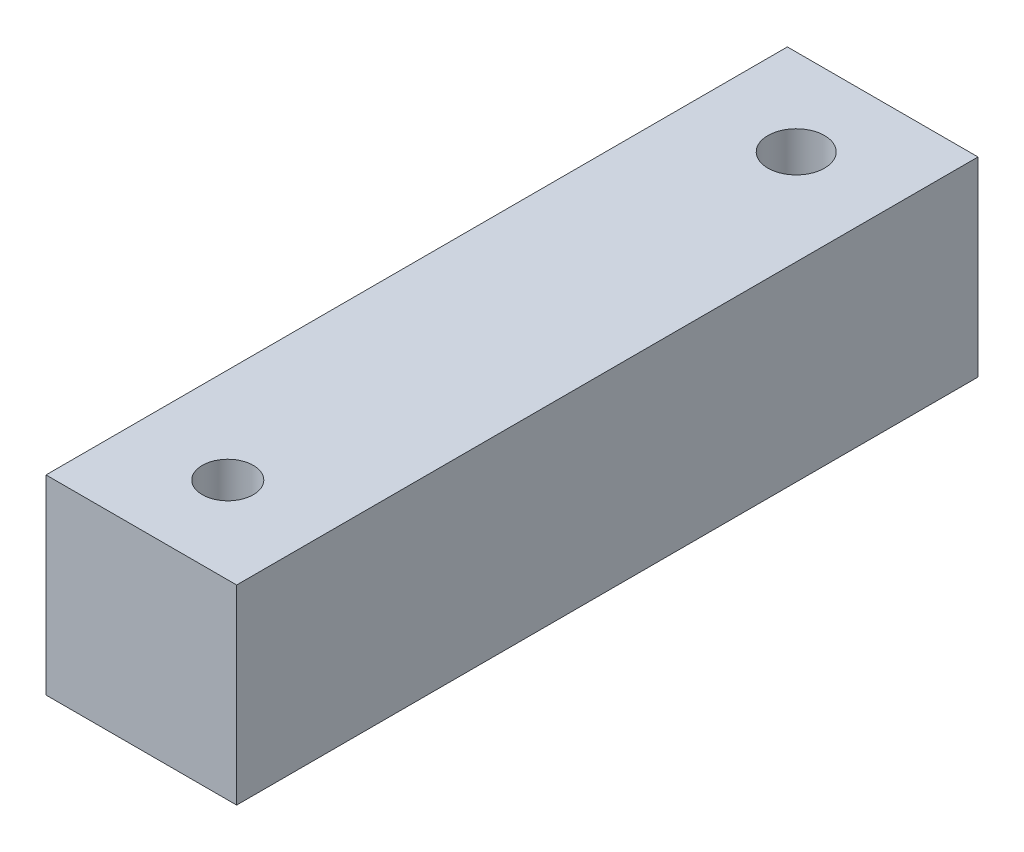
SolidWorks part; units mm, degrees
ref_plane "Plan de face" through (0, 0, 0) normal (0, 0, 1) x (1, 0, 0)
ref_plane "Plan de dessus" through (0, 0, 0) normal (0, 1, 0) x (1, 0, 0)
ref_plane "Plan de droite" through (0, 0, 0) normal (1, 0, 0) x (0, 0, -1)
sketch "Esquisse1" plane through (0, 0, 0) normal (0, 0, 1) x (1, 0, 0)
  line L1 (0, 18) -> (18, 18)
  line L2 (0, 18) -> (0, 0)
  line L3 (0, 0) -> (18, 0)
  line L4 (18, 18) -> (18, 0)
  dimension "D1" = 18
extrude "Boss.-Extru.1" add sketch "Esquisse1" along normal blind 70
sketch "Esquisse4" plane through (0, 18, 0) normal (0, 1, 0) x (1, 0, 0)
  line L0 (18, -70) -> (0, -70) construction
  line L1 (9, -61.836) -> (9, -70) construction
  line L2 (9, -8.164) -> (9, 0) construction
  line L3 (18, 0) -> (0, 0) construction
  circle A0 centre (9, -61.836) radius 2.4071
  circle A1 centre (9, -8.164) radius 2.6729
extrude "Enlèv. mat.-Extru.1" cut sketch "Esquisse4" against normal blind 50
